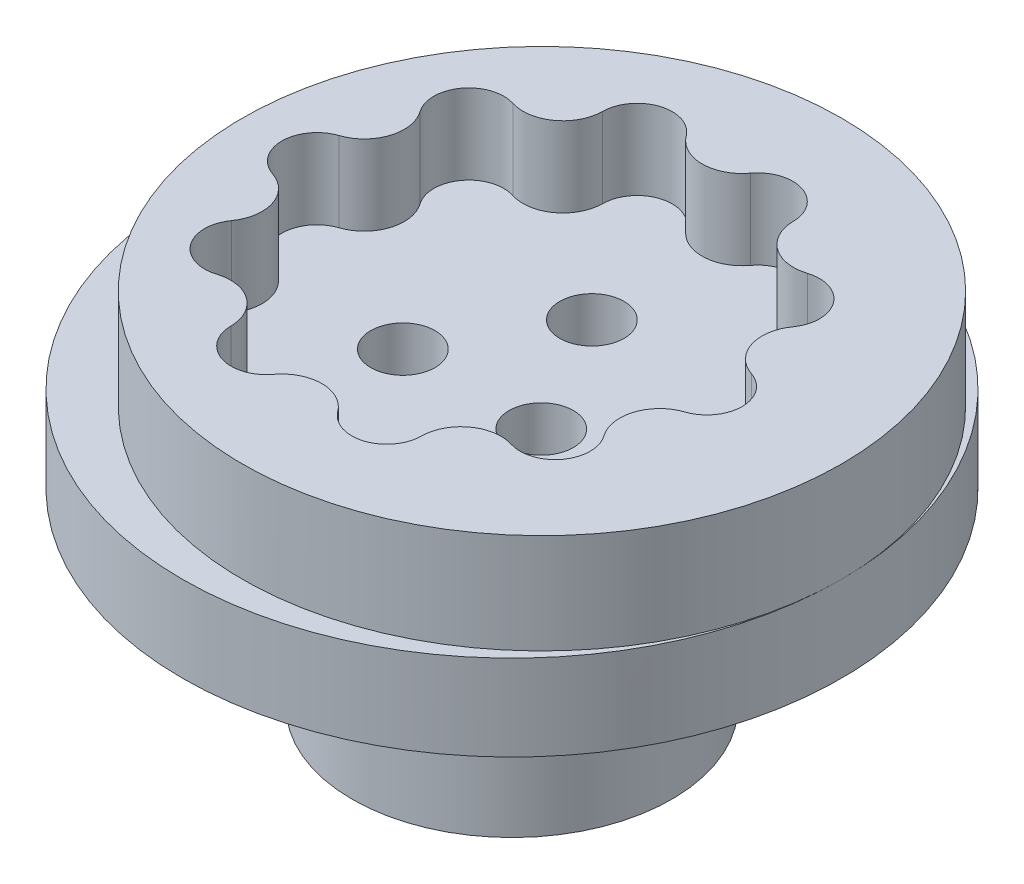
SolidWorks part; units mm, degrees
material "6061 Alloy"
ref_plane "Front" through (0, 0, 0) normal (0, 0, 1) x (1, 0, 0)
ref_plane "Top" through (0, 0, 0) normal (0, 1, 0) x (1, 0, 0)
ref_plane "Right" through (0, 0, 0) normal (1, 0, 0) x (0, 0, -1)
sketch "Sketch1" plane through (0, 0, 0) normal (0, 1, 0) x (1, 0, 0)
  circle A0 centre (0, 0) radius 26.1937
  dimension "D1" = 52.3875
extrude "Boss-Extrude1" add sketch "Sketch1" against normal blind 8.3979
sketch "Sketch2" plane through (0, -8.3979, 0) normal (0, -1, 0) x (1, 0, 0)
  circle A0 centre (0, 0) radius 12.7
  dimension "D1" = 25.4
extrude "Boss-Extrude2" add sketch "Sketch2" along normal blind 15.0812
sketch "Sketch3" plane through (0, 0, 0) normal (0, 1, 0) x (1, 0, 0)
  line L0 (0, 0) -> (0, 26.1938) construction
  line L1 (0, 0) -> (15.3963, 21.1912) construction
  arc A0 (2.553, 16.4005) -> (7.5745, 14.7689) centre (4.7912, 14.7457) cw
  circle A1 centre (0, 0) radius 26.1938 construction
  circle A2 centre (0, 0) radius 18.288 construction
  arc A3 (0, 15.113) -> (2.553, 16.4005) centre (0, 18.288) ccw
  arc A4 (8.8832, 12.2267) -> (7.5745, 14.7689) centre (10.7494, 14.7953) cw
  arc A5 (8.8832, 12.2267) -> (11.7054, 11.7676) centre (10.7494, 14.7953) ccw
  arc A6 (11.7054, 11.7676) -> (14.8088, 7.4961) centre (12.5434, 9.1133) cw
  arc A7 (14.3733, 4.6702) -> (14.8088, 7.4961) centre (17.3929, 5.6513) cw
  arc A8 (14.3733, 4.6702) -> (16.3867, 2.64) centre (17.3929, 5.6513) ccw
  arc A9 (16.3867, 2.64) -> (16.3867, -2.64) centre (15.5045, 0) cw
  arc A10 (14.3733, -4.6702) -> (16.3867, -2.64) centre (17.3929, -5.6513) cw
  arc A11 (14.3733, -4.6702) -> (14.8088, -7.4961) centre (17.3929, -5.6513) ccw
  arc A12 (14.8088, -7.4961) -> (11.7054, -11.7676) centre (12.5434, -9.1133) cw
  arc A13 (8.8832, -12.2267) -> (11.7054, -11.7676) centre (10.7494, -14.7953) cw
  arc A14 (8.8832, -12.2267) -> (7.5745, -14.7689) centre (10.7494, -14.7953) ccw
  arc A15 (7.5745, -14.7689) -> (2.553, -16.4005) centre (4.7912, -14.7457) cw
  arc A16 (0, -15.113) -> (2.553, -16.4005) centre (0, -18.288) cw
  arc A17 (0, -15.113) -> (-2.553, -16.4005) centre (0, -18.288) ccw
  arc A18 (-2.553, -16.4005) -> (-7.5745, -14.7689) centre (-4.7912, -14.7457) cw
  arc A19 (-8.8832, -12.2267) -> (-7.5745, -14.7689) centre (-10.7494, -14.7953) cw
  arc A20 (-8.8832, -12.2267) -> (-11.7054, -11.7676) centre (-10.7494, -14.7953) ccw
  arc A21 (-11.7054, -11.7676) -> (-14.8088, -7.4961) centre (-12.5434, -9.1133) cw
  arc A22 (-14.3733, -4.6702) -> (-14.8088, -7.4961) centre (-17.3929, -5.6513) cw
  arc A23 (-14.3733, -4.6702) -> (-16.3867, -2.64) centre (-17.3929, -5.6513) ccw
  arc A24 (-16.3867, -2.64) -> (-16.3867, 2.64) centre (-15.5045, 0) cw
  arc A25 (-14.3733, 4.6702) -> (-16.3867, 2.64) centre (-17.3929, 5.6513) cw
  arc A26 (-14.3733, 4.6702) -> (-14.8088, 7.4961) centre (-17.3929, 5.6513) ccw
  arc A27 (-14.8088, 7.4961) -> (-11.7054, 11.7676) centre (-12.5434, 9.1133) cw
  arc A28 (-8.8832, 12.2267) -> (-11.7054, 11.7676) centre (-10.7494, 14.7953) cw
  arc A29 (-8.8832, 12.2267) -> (-7.5745, 14.7689) centre (-10.7494, 14.7953) ccw
  arc A30 (-7.5745, 14.7689) -> (-2.553, 16.4005) centre (-4.7912, 14.7457) cw
  arc A31 (0, 15.113) -> (-2.553, 16.4005) centre (0, 18.288) cw
  circle A32 centre (0, 0) radius 26.1938
  point P78 (0, 0)
  dimension "D1" = 36.576
  dimension "D2" = 3.175
  dimension "D3" = 36
extrude "Boss-Extrude3" add sketch "Sketch3" along normal blind 6.35
hole_wizard "1/4-20 Tapped Hole1" positions "Sketch5" profile "Sketch4" tap size "1/4-20" standard "ANSI Inch" end condition through all
sketch "Sketch5" plane through (0, -23.4791, 0) normal (0, -1, 0) x (-1, 0, 0)
  circle A1 centre (0, 0) radius 6.35
  circle A3 centre (0, 0) radius 12.7 construction
  point P2 (0, 6.35)
  point P23 (5.4993, -3.175)
  point P24 (-5.4993, -3.175)
  dimension "D1" = 12.7
  dimension "D2" = 3
sketch "Sketch4" plane through (0, -23.4791, -6.35) normal (1, 0, 0) x (0, 0, -1)
  line L0 (0, 0) -> (0, 29.8291)
  line L1 (0, 29.8291) -> (2.5527, 29.8291)
  line L2 (2.5527, 29.8291) -> (2.5527, 0)
  line L5 (2.5527, 0) -> (0, 0)
  line L11 (0, -6.35) -> (0, 107.95) construction
  dimension "Thread Major Dia." = 5.1054
  dimension "Thru Tap Drill Depth" = 29.8291
sketch "Sketch6" plane through (0, 6.35, 0) normal (0, 1, 0) x (1, 0, 0)
  line L0 (-26.1938, 0) -> (26.1938, 0) construction
  line L2 (-33.2518, 33.8083) -> (33.2518, 33.8083)
  line L3 (-33.2518, 33.8083) -> (-33.2518, -33.8083)
  line L4 (-33.2518, -33.8083) -> (33.2518, -33.8083)
  line L5 (33.2518, 33.8083) -> (33.2518, -33.8083)
  line L6 (-33.2518, 33.8083) -> (33.2518, -33.8083) construction
  line L7 (-33.2518, -33.8083) -> (33.2518, 33.8083) construction
  circle A0 centre (0, 0) radius 26.1938 construction
  arc A1 (26.1938, 0) -> (-21.4313, 0) centre (2.3812, 0) cw
  arc A2 (26.1938, 0) -> (-21.4313, 0) centre (2.3812, 0) ccw
  point P7 (0, 0)
  dimension "D1" = 4.7625
extrude "Cut-Extrude2" cut sketch "Sketch6" against normal blind 7.9375
